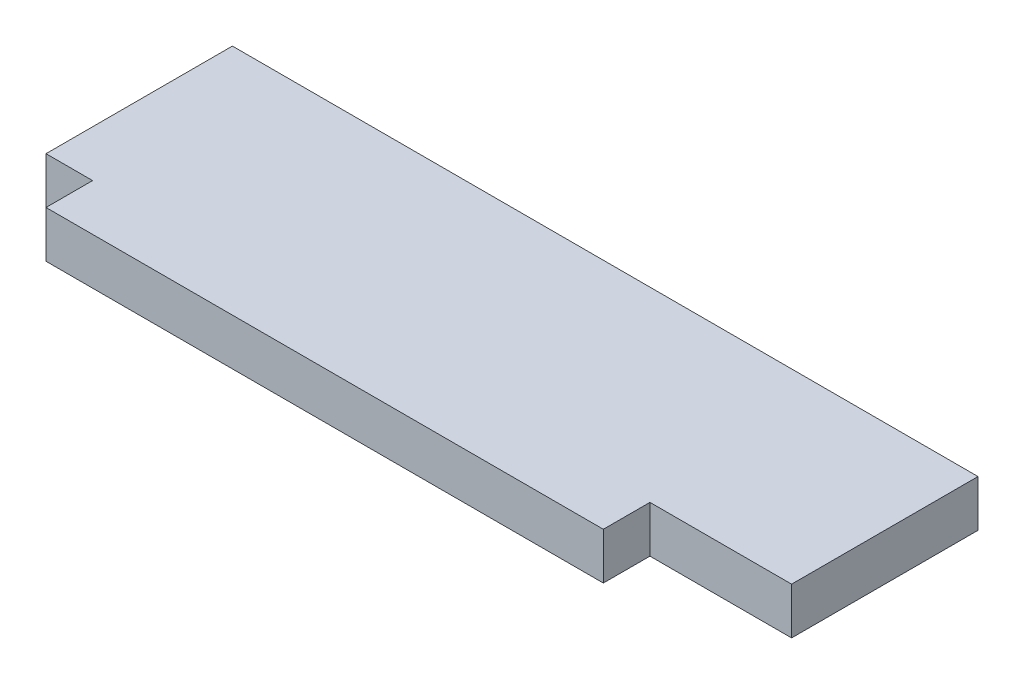
SolidWorks part; units mm, degrees
ref_plane "Front Plane" through (0, 0, 0) normal (0, 0, 1) x (1, 0, 0)
ref_plane "Top Plane" through (0, 0, 0) normal (0, 1, 0) x (1, 0, 0)
ref_plane "Right Plane" through (0, 0, 0) normal (1, 0, 0) x (0, 0, -1)
sketch "Sketch1" plane through (0, 0, 0) normal (0, 1, 0) x (1, 0, 0)
  line L1 (0, 0) -> (80, 0)
  line L2 (0, 0) -> (0, 20)
  line L3 (0, 20) -> (80, 20)
  line L4 (80, 0) -> (80, 20)
  line L5 (5, 0) -> (64.8, 0)
  line L6 (5, 0) -> (5, -5)
  line L7 (5, -5) -> (64.8, -5)
  line L8 (64.8, 0) -> (64.8, -5)
  dimension "D1" = 80
  dimension "D2" = 20
  dimension "D3" = 59.8
  dimension "D4" = 5
  dimension "D5" = 5
extrude "Boss-Extrude1" add sketch "Sketch1" along normal blind 5 contours L1 L4 L3 L2 | L8 L1 L6 L7
